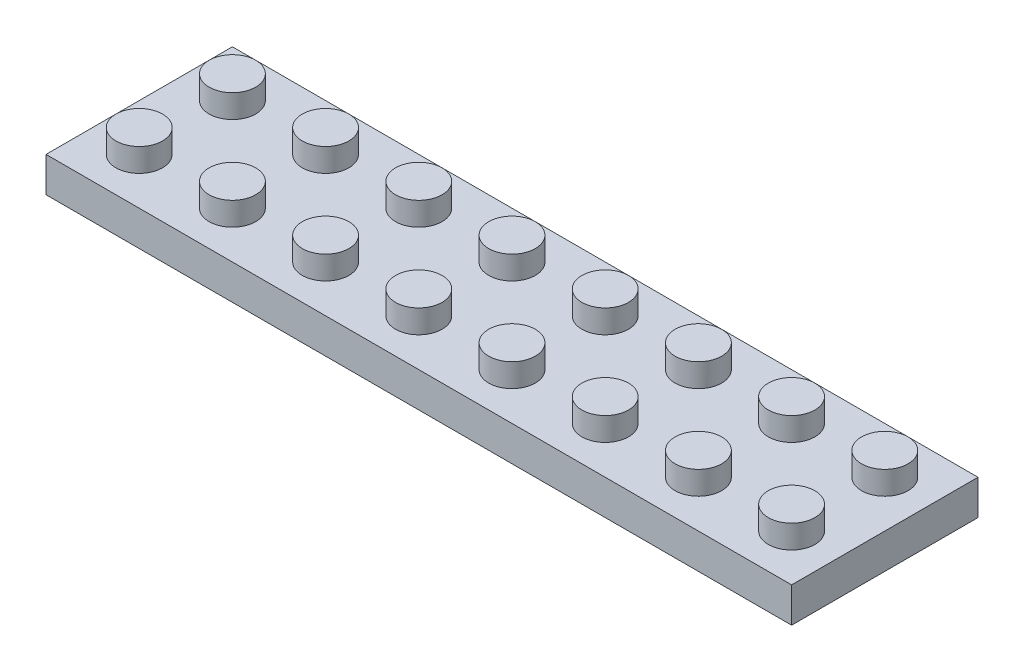
SolidWorks part; units mm, degrees
ref_plane "Front Plane" through (0, 0, 0) normal (0, 0, 1) x (1, 0, 0)
ref_plane "Top Plane" through (0, 0, 0) normal (0, 1, 0) x (1, 0, 0)
ref_plane "Right Plane" through (0, 0, 0) normal (1, 0, 0) x (0, 0, -1)
sketch "Sketch1" plane through (0, 0, 0) normal (0, 1, 0) x (1, 0, 0)
  line L1 (-32, -8) -> (32, -8)
  line L2 (-32, -8) -> (-32, 8)
  line L3 (-32, 8) -> (32, 8)
  line L4 (32, -8) -> (32, 8)
  line L5 (-32, -8) -> (32, 8) construction
  line L6 (-32, 8) -> (32, -8) construction
  point P0 (0, 0)
  dimension "D1" = 16
  dimension "D2" = 64
extrude "Boss-Extrude1" add sketch "Sketch1" along normal blind 3
sketch "Sketch2" plane through (0, 3, 0) normal (0, 1, 0) x (1, 0, 0)
  line L0 (-32, 8) -> (-32, -8) construction
  line L1 (32, 8) -> (-32, 8) construction
  circle A0 centre (-28, 4) radius 2
  circle A1 centre (-20, 4) radius 2
  circle A2 centre (-12, 4) radius 2
  circle A3 centre (-4, 4) radius 2
  circle A4 centre (4, 4) radius 2
  circle A5 centre (12, 4) radius 2
  circle A6 centre (20, 4) radius 2
  circle A7 centre (28, 4) radius 2
  circle A8 centre (-20, -4) radius 2
  circle A9 centre (-12, -4) radius 2
  circle A10 centre (-4, -4) radius 2
  circle A11 centre (4, -4) radius 2
  circle A12 centre (12, -4) radius 2
  circle A13 centre (20, -4) radius 2
  circle A14 centre (28, -4) radius 2
  circle A15 centre (-28, -4) radius 2
  dimension "D1" = 4
  dimension "D2" = 4
  dimension "D3" = 4
  dimension "D4" = 8
  dimension "D5" = 2
extrude "Boss-Extrude2" add sketch "Sketch2" along normal blind 2
shell "Shell1" thickness 1
sketch "Sketch3" plane through (0, 2, 0) normal (0, -1, 0) x (1, 0, 0)
  line L0 (-32, -8) -> (-32, 8) construction
  circle A0 centre (-24, 0) radius 1.8
  circle A1 centre (-24, 0) radius 2.8
  dimension "D1" = 3.6
  dimension "D2" = 5.6
  dimension "D3" = 8
extrude "Boss-Extrude3" add sketch "Sketch3" along normal blind 2
pattern_linear "LPattern1" count 7 spacing 8 along (1, 0, 0) of "Boss-Extrude3"
